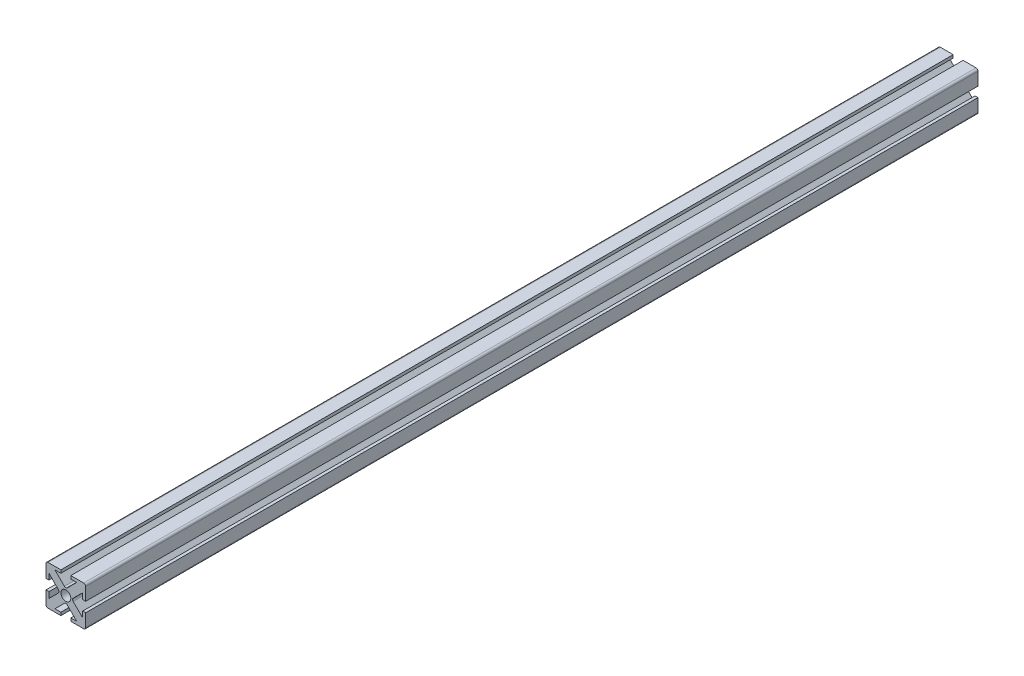
SolidWorks part; units mm, degrees
ref_plane "前基準面" through (0, 0, 0) normal (0, 0, 1) x (1, 0, 0)
ref_plane "上基準面" through (0, 0, 0) normal (0, 1, 0) x (1, 0, 0)
ref_plane "右基準面" through (0, 0, 0) normal (1, 0, 0) x (0, 0, -1)
sketch "草圖1" plane through (0, 0, 0) normal (0, 0, 1) x (1, 0, 0)
  line L0 (-2500, 10000) -> (-2500, 8500)
  line L1 (-10000, 10000) -> (-2500, 10000)
  line L2 (-10000, 10000) -> (-10000, 2500)
  line L3 (-10000, -10000) -> (-2500, -10000)
  line L4 (10000, 10000) -> (10000, 2500)
  line L5 (-10000, 10000) -> (10000, -10000) construction
  line L6 (-10000, -10000) -> (10000, 10000) construction
  line L7 (-2500, 8500) -> (-5500, 8500)
  line L8 (-5500, 8500) -> (0, 3000)
  line L9 (0, 3000) -> (5500, 8500)
  line L10 (5500, 8500) -> (2500, 8500)
  line L11 (2500, 8500) -> (2500, 10000)
  line L12 (0, 10000) -> (0, -11814.1698) construction
  line L13 (8500, 2500) -> (8500, 5500)
  line L14 (8500, -2500) -> (10000, -2500)
  line L15 (10000, 2500) -> (8500, 2500)
  line L16 (8500, 5500) -> (3000, 0)
  line L17 (3000, 0) -> (8500, -5500)
  line L18 (8500, -5500) -> (8500, -2500)
  line L19 (2500, -8500) -> (5500, -8500)
  line L20 (-2500, -8500) -> (-2500, -10000)
  line L21 (2500, -10000) -> (2500, -8500)
  line L22 (5500, -8500) -> (0, -3000)
  line L23 (0, -3000) -> (-5500, -8500)
  line L24 (-5500, -8500) -> (-2500, -8500)
  line L25 (-8500, -2500) -> (-8500, -5500)
  line L26 (-8500, 2500) -> (-10000, 2500)
  line L27 (-10000, -2500) -> (-8500, -2500)
  line L28 (-8500, -5500) -> (-3000, 0)
  line L29 (-3000, 0) -> (-8500, 5500)
  line L30 (-8500, 5500) -> (-8500, 2500)
  line L31 (2500, 10000) -> (10000, 10000)
  line L32 (10000, -2500) -> (10000, -10000)
  line L33 (2500, -10000) -> (10000, -10000)
  line L34 (-10000, -2500) -> (-10000, -10000)
  circle A0 centre (0, 0) radius 2500
  point P0 (0, 0)
  point P17 (-35162.9044, -1332.4278)
  point P41 (0, 0)
  dimension "D3" = 5000
  dimension "D2" = 20000
  dimension "D4" = 5000
  dimension "D5" = 3000
  dimension "D6" = 1500
  dimension "D7" = 4
extrude "填料-伸長1" add sketch "草圖1" along normal blind 450000
fillet "圓角1" radius 1000 4 edges at (0, -3000, 225000) (-3000, 0, 225000) (3000, 0, 225000) (0, 3000, 225000)
fillet "圓角2" radius 1000 4 edges at (-10000, 10000, 225000) (10000, 10000, 225000) (10000, -10000, 225000) (-10000, -10000, 225000)
